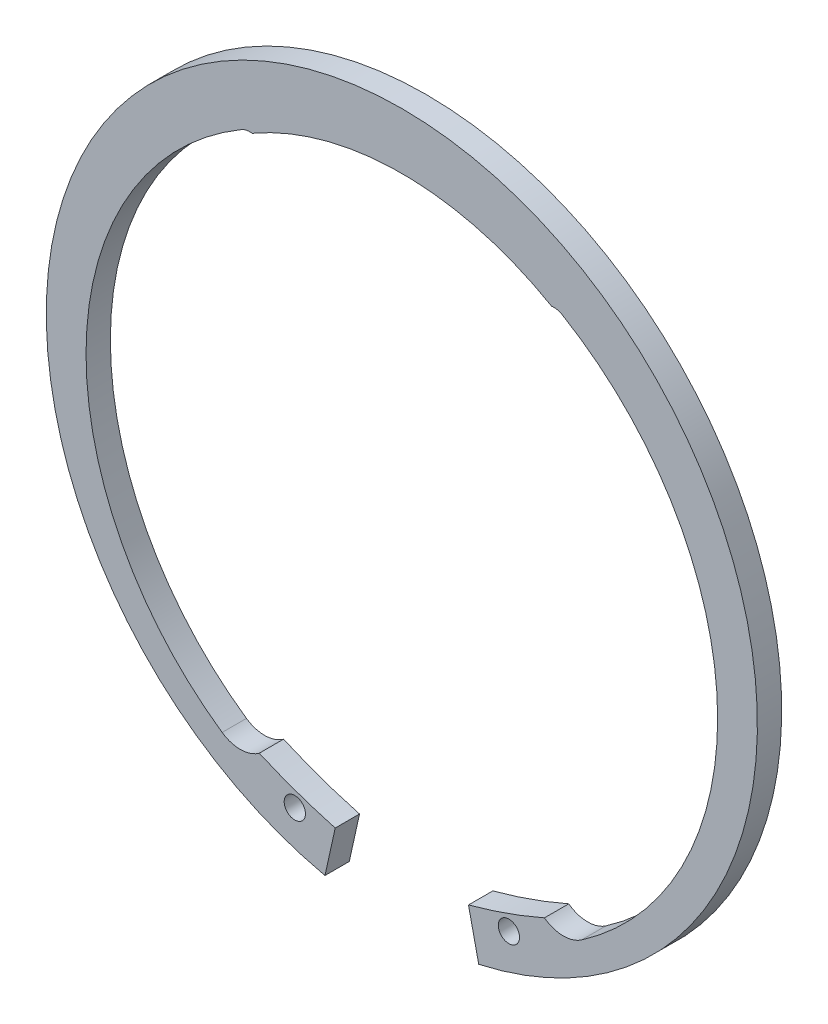
SolidWorks part; units mm, degrees
ref_plane "Front Plane" through (0, 0, 0) normal (0, 0, 1) x (1, 0, 0)
ref_plane "Top Plane" through (0, 0, 0) normal (0, 1, 0) x (1, 0, 0)
ref_plane "Right Plane" through (0, 0, 0) normal (1, 0, 0) x (0, 0, -1)
sketch "Sketch1" plane through (0, 0, 0) normal (0, 0, 1) x (1, 0, 0)
  line L0 (0, 58.5) -> (0, 49.5) construction
  line L1 (-32.0318, -48.9511) -> (-29.5678, -45.1856) construction
  line L2 (0, 0) -> (0, -58.5) construction
  line L3 (-10.4, -46.9622) -> (-12.6486, -57.1162) construction
  line L4 (-10.4, -46.9622) -> (-13.9, -46.9622) construction
  circle A0 centre (0, 0) radius 57 construction
  circle A1 centre (0, 0) radius 58.5 construction
  circle A2 centre (0, 0) radius 55 construction
  dimension "Ring OD" = 117
  dimension "For ID" = 110
  dimension "Maximum Section" = 9
  dimension "Maximum Lug Height" = 10.4
  dimension "Hole Diameter" = 3.5
  dimension "D2" = 4.5
  dimension "Gap Width" = 20.8
  dimension "D1" = 19.25
sketch "Sketch2" plane through (0, 0, 0) normal (1, 0, 0) x (0, 0, -1)
  line L0 (-2.075, 58.5) -> (2.075, 58.5) construction
  line L1 (-2, -58.5) -> (2, -58.5) construction
  point P3 (0, 58.5)
  point P7 (0, -58.5)
  point P8 (-2, -58.5)
  point P10 (2, -58.5)
  point P11 (-2.075, 58.5)
  point P12 (2.075, 58.5)
  dimension "For Groove Width" = 4.15
  dimension "Ring Thickness" = 4
sketch "Sketch3" plane through (0, 0, 0) normal (0, 0, 1) x (1, 0, 0)
  line L0 (-12.6486, -57.1162) -> (-10.9622, -49.5007)
  line L1 (-10.9622, -49.5007) -> (-23.4623, -45.0924)
  line L2 (0, 0) -> (-16.7385, -47.4636) construction
  line L3 (-29.5678, -45.1856) -> (29.5678, -45.1856) construction
  line L4 (0, 0) -> (0, -58.5) construction
  line L7 (-17.6115, -49.9392) -> (-16.7385, -47.4636) construction
  line L8 (0, 58.5) -> (0, 49.5) construction
  line L9 (10.9622, -49.5007) -> (23.4623, -45.0924)
  line L10 (12.6486, -57.1162) -> (10.9622, -49.5007)
  line L12 (-10.4, -46.9622) -> (-12.6486, -57.1162) construction
  arc A0 (-12.6486, -57.1162) -> (12.6486, -57.1162) centre (0, 0) cw
  circle A1 centre (0, 0) radius 58.5 construction
  arc A2 (-29.5678, -45.1856) -> (29.5678, -45.1856) centre (0, -2.4595) cw
  arc A3 (-29.5678, -45.1856) -> (-23.4623, -45.0924) centre (-26.5803, -40.8686) ccw
  circle A4 centre (-17.6115, -49.9392) radius 1.75
  circle A5 centre (0, 0) radius 54 construction
  arc A6 (29.5678, -45.1856) -> (23.4623, -45.0924) centre (26.5803, -40.8686) cw
  circle A7 centre (17.6115, -49.9392) radius 1.75
  point P3 (0, -45.1856)
  dimension "D1" = 3.5
  dimension "D5" = 5.25
  dimension "D2" = 6.125
  dimension "D3" = 7.8
  dimension "D4" = 2.625
extrude "Boss-Extrude1" add sketch "Sketch3" against normal up to vertex (2 mm away) and the other way up to vertex (2 mm away) up to point (0, -58.5, -2) other way up to point (0, -58.5, 2)
sketch "Sketch6" plane through (0, 0, 0) normal (0, 0, 1) x (1, 0, 0)
  line L0 (0, 0) -> (-24.625, 42.6518) construction
  line L1 (24.625, 42.6518) -> (0, 0) construction
  line L2 (0, 0) -> (0, -58.5) construction
  line L3 (-26.4204, 42.2814) -> (0, 0) construction
  arc A0 (-24.625, 42.6518) -> (24.625, 42.6518) centre (0, 0) cw
  circle A1 centre (0, 0) radius 57 construction
  arc A2 (-24.625, 42.6518) -> (-26.4204, 42.2814) centre (-24.9822, 39.846) ccw
  arc A3 (29.5678, -45.1856) -> (-29.5678, -45.1856) centre (0, -2.4595) ccw construction
  arc A4 (24.625, 42.6518) -> (26.4204, 42.2814) centre (24.9822, 39.846) cw
  arc A5 (-26.4204, 42.2814) -> (26.4204, 42.2814) centre (0, -2.4595) cw
  point P3 (0, 49.25)
  dimension "D1" = 0.25
  dimension "D3" = 2
  dimension "D2" = 30
extrude "Boss-Extrude2" add sketch "Sketch6" along normal up to surface and the other way up to surface
sketch "Sketch5" plane through (0, 0, 0) normal (0, 0, 1) x (1, 0, 0)
  line L1 (-23.4623, -45.0924) -> (0, 0)
  line L2 (0, 0) -> (-10.9622, -49.5007)
  line L3 (-10.9622, -49.5007) -> (-23.4623, -45.0924) construction
  arc A0 (-23.4623, -45.0924) -> (-10.9622, -49.5007) centre (11.9616, 35.4287) ccw
  arc A3 (-29.5678, -45.1856) -> (-23.4623, -45.0924) centre (-26.5803, -40.8686) ccw construction
  point P3 (-17.2954, -47.5323)
  dimension "D1" = 0.25
extrude "Cut-Extrude2" cut sketch "Sketch5" against normal through all both and the other way through all
mirror "Mirror1" about plane through (0, 0, 0) normal (1, 0, 0) of "Cut-Extrude2"
equation "\"D1@Sketch3\"=\"Hole Diameter@Sketch1\""
equation "\"D2@Sketch3\"=\"Hole Diameter@Sketch1\"*1.75"
equation "\"D2@Sketch1\"=\"Maximum Section@Sketch1\"*.5"
equation "\"Gap Width@Sketch1\" = \"Maximum Lug Height@Sketch1\" * 2"
equation "\"D3@Sketch3\" = \"Maximum Lug Height@Sketch1\" * .75"
equation "\"D4@Sketch3\"=\"Hole Diameter@Sketch1\"*.75"
equation "\"D1@Sketch1\"=\"Hole Diameter@Sketch1\"*5.5"
equation "\"D5@Sketch3\"=\"Hole Diameter@Sketch1\"*1.5"
